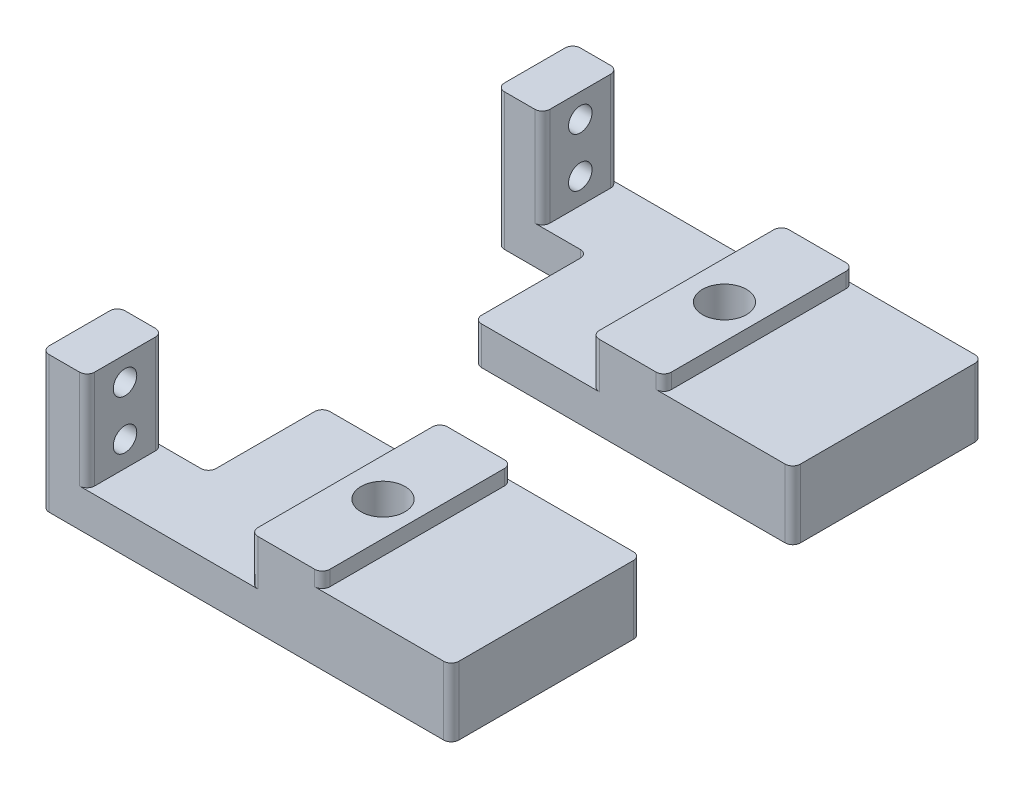
SolidWorks part; units mm, degrees
other "Left Hand"
other "Right Hand"
ref_plane "Front Plane" through (0, 0, 0) normal (0, 0, 1) x (1, 0, 0)
ref_plane "Top Plane" through (0, 0, 0) normal (0, 1, 0) x (1, 0, 0)
ref_plane "Right Plane" through (0, 0, 0) normal (1, 0, 0) x (0, 0, -1)
sketch "Sketch1" plane through (0, 0, 0) normal (0, 1, 0) x (1, 0, 0)
  line L1 (0, 0) -> (45, 0)
  line L2 (0, 0) -> (0, 25)
  line L3 (0, 25) -> (45, 25)
  line L4 (45, 0) -> (45, 25)
  dimension "D1" = 45
  dimension "D2" = 25
extrude "Boss-Extrude1" add sketch "Sketch1" along normal blind 5 contours L1 L4 L3 L2
sketch "Sketch5" plane through (0, 5, 0) normal (0, 1, 0) x (1, 0, 0)
  line L0 (0, 25) -> (45, 25) construction
  line L1 (18.5, 25) -> (45, 25)
  line L2 (18.5, 25) -> (18.5, 0)
  line L3 (18.5, 0) -> (45, 0)
  line L4 (45, 25) -> (45, 0)
  line L5 (45, 0) -> (45, 25) construction
  line L6 (0, 0) -> (45, 0) construction
  dimension "D1" = 26.5
extrude "Boss-Extrude3" add sketch "Sketch5" along normal blind 4
sketch "Sketch11" plane through (0, 9, 0) normal (0, 1, 0) x (1, 0, 0)
  line L0 (18.5, 25) -> (18.5, 0) construction
  line L1 (18.5, 25) -> (28, 25)
  line L2 (18.5, 25) -> (18.5, 0)
  line L3 (18.5, 0) -> (28, 0)
  line L4 (28, 25) -> (28, 0)
  line L5 (45, 25) -> (18.5, 25) construction
  line L6 (18.5, 0) -> (45, 0) construction
  dimension "D1" = 9.5
extrude "Boss-Extrude5" add sketch "Sketch11" along normal blind 2
sketch "Sketch12" plane through (0, 5, 0) normal (0, 1, 0) x (1, 0, 0)
  line L0 (0, 25) -> (18.5, 25) construction
  line L1 (0, 25) -> (3, 25)
  line L2 (0, 25) -> (0, 0)
  line L3 (0, 0) -> (3, 0)
  line L4 (3, 25) -> (3, 0)
  line L5 (0, 0) -> (0, 25) construction
  line L6 (0, 0) -> (18.5, 0) construction
  dimension "D1" = 3
extrude "Cut-Extrude2" cut sketch "Sketch12" against normal through all
sketch "Sketch13" plane through (0, 0, 0) normal (0, -1, 0) x (-1, 0, 0)
  line L0 (-23.5, 0) -> (-23.5, 25) construction
  line L1 (-3, 0) -> (-45, 0) construction
  line L2 (-3, 25) -> (-45, 25) construction
  line L3 (-45, 0) -> (-45, 25) construction
  point P8 (-23.5, 12.5)
  dimension "D1" = 21.5
hole_wizard "M5 Clearance Hole1" positions "Sketch14" profile "Sketch15" hole size "M5" standard "ISO" end condition through all
sketch "Sketch14" plane through (0, 0, 0) normal (0, -1, 0) x (-1, 0, 0)
  point P0 (-23.5, 12.5)
sketch "Sketch15" plane through (23.5, 0, -12.5) normal (1, 0, 0) x (0, 0, -1)
  line L0 (0, 0) -> (0, 11)
  line L1 (0, 11) -> (2.9, 11)
  line L2 (2.9, 11) -> (2.9, 0)
  line L5 (2.9, 0) -> (0, 0)
  line L11 (0, -6.35) -> (0, 107.95) construction
  dimension "Thru Hole Dia." = 5.8
  dimension "Thru Hole Depth" = 11
sketch "Sketch18" plane through (0, 0, -25) normal (0, 0, -1) x (-1, 0, 0)
  line L0 (-3, 5) -> (-18.5, 5) construction
  line L1 (-3, 0) -> (9, 0)
  line L2 (-3, 0) -> (-3, 5)
  line L3 (-3, 5) -> (3, 5)
  line L7 (9, 0) -> (9, 18)
  line L8 (9, 18) -> (3, 18)
  line L9 (3, 5) -> (3, 18)
  dimension "D1" = 12
  dimension "D2" = 6
  dimension "D3" = 13
extrude "Boss-Extrude8" add sketch "Sketch18" against normal blind 10
sketch "Sketch19" plane through (-9, 0, 0) normal (-1, 0, 0) x (0, 0, 1)
  line L0 (-20, 18) -> (-20, 8.35) construction
  line L1 (-15, 18) -> (-25, 18) construction
  point P1 (-20, 8.35)
  point P4 (-20, 14.85)
  dimension "D1" = 3.15
  dimension "D2" = 6.5
hole_wizard "M2.5 Clearance Hole1" positions "Sketch19" profile "Sketch20" hole size "M2.5" standard "ISO"
sketch "Sketch20" plane through (-9, 14.85, -20) normal (0, 1, 0) x (0, 0, 1)
  line L0 (0, 0) -> (0, 6.9313)
  line L1 (0, 6.9313) -> (1.55, 6)
  line L2 (1.55, 6) -> (1.55, 0)
  line L5 (1.55, 0) -> (0, 0)
  line L10 (0, 6.9313) -> (-1.55, 6) construction
  line L11 (0, -6.35) -> (0, 107.95) construction
  dimension "Hole Dia." = 3.1
  dimension "Hole Depth" = 6
  dimension "Drill Angle" = 118
fillet "Fillet2" radius 1 12 edges at (28, 10, 0) (18.5, 8, 0) (18.5, 8, -25) (28, 10, -25) (3, 2.5, 0) (45, 4.5, 0) (45, 4.5, -25) (-3, 11.5, -25) (-3, 11.5, -15) (-9, 9, -25) (-9, 9, -15) (3, 2.5, -15)
ref_plane "Plane1" through (0, 0, 10) normal (0, 0, 1) x (1, 0, 0)
mirror "Mirror2" about plane through (0, 0, 10) normal (0, 0, 1) of bodies 113
